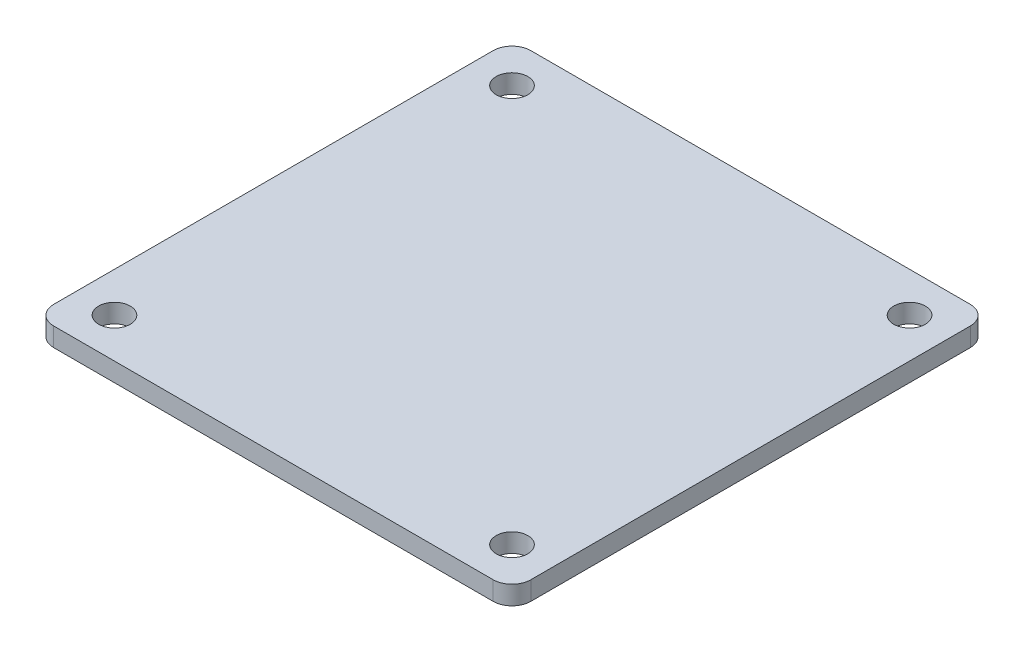
SolidWorks part; units mm, degrees
ref_plane "Front Plane" through (0, 0, 0) normal (0, 0, 1) x (1, 0, 0)
ref_plane "Top Plane" through (0, 0, 0) normal (0, 1, 0) x (1, 0, 0)
ref_plane "Right Plane" through (0, 0, 0) normal (1, 0, 0) x (0, 0, -1)
sketch "Sketch1" plane through (0, 0, 0) normal (0, 1, 0) x (1, 0, 0)
  line L1 (-38.1, -38.1) -> (38.1, -38.1)
  line L2 (-38.1, -38.1) -> (-38.1, 38.1)
  line L3 (-38.1, 38.1) -> (38.1, 38.1)
  line L4 (38.1, -38.1) -> (38.1, 38.1)
  line L5 (-38.1, -38.1) -> (38.1, 38.1) construction
  line L6 (-38.1, 38.1) -> (38.1, -38.1) construction
  circle A0 centre (-31.75, 31.75) radius 2.525
  circle A1 centre (31.75, 31.75) radius 2.525
  circle A2 centre (31.75, -31.75) radius 2.525
  circle A3 centre (-31.75, -31.75) radius 2.525
  point P0 (0, 0)
  point P11 (0, 0)
  point P14 (0, 0)
  point P17 (0, 0)
  point P20 (0, 0)
  dimension "D3" = 6.35
  dimension "D4" = 5.05
  dimension "D1" = 76.2
  dimension "D2" = 76.2
  dimension "D5" = 4
extrude "Boss-Extrude1" add sketch "Sketch1" along normal blind 3
fillet "Fillet1" radius 3 4 edges at (38.1, 1.5, 38.1) (38.1, 1.5, -38.1) (-38.1, 1.5, -38.1) (-38.1, 1.5, 38.1)
